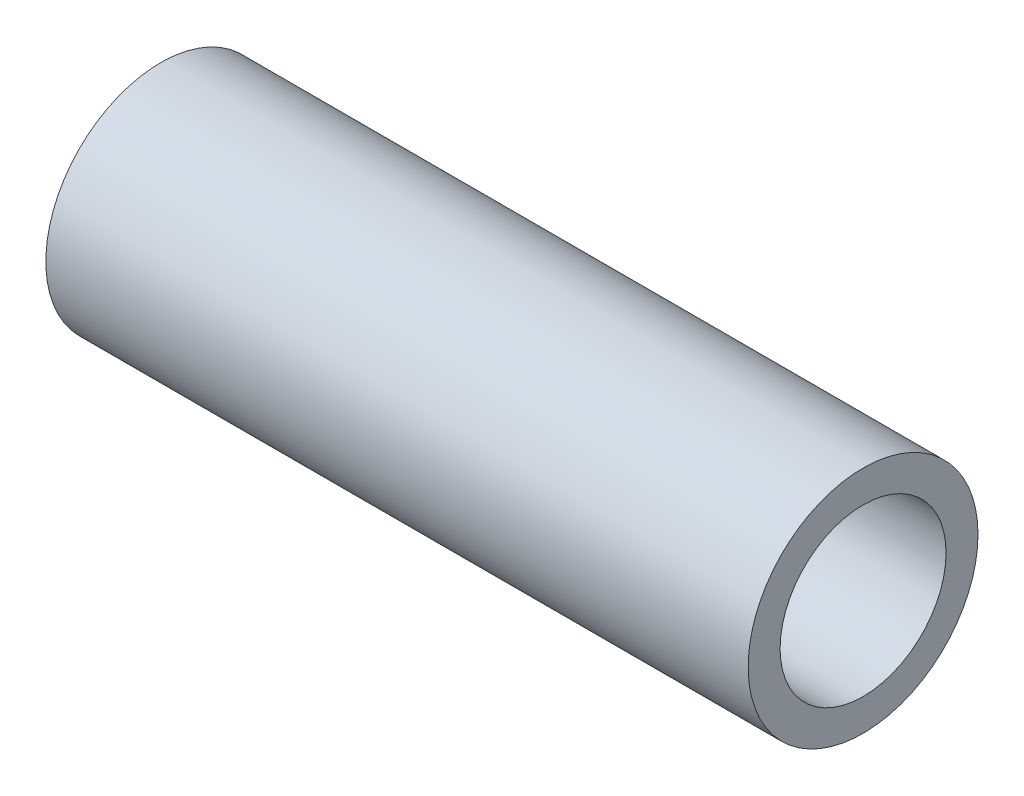
SolidWorks part; units mm, degrees
ref_plane "Front Plane" through (0, 0, 0) normal (0, 0, 1) x (1, 0, 0)
ref_plane "Top Plane" through (0, 0, 0) normal (0, 1, 0) x (1, 0, 0)
ref_plane "Right Plane" through (0, 0, 0) normal (1, 0, 0) x (0, 0, -1)
sketch "Sketch1" plane through (0, 0, 0) normal (1, 0, 0) x (0, 0, -1)
  circle A0 centre (0, 0) radius 6.5
  circle A1 centre (0, 0) radius 9
  dimension "D1" = 18
  dimension "D2" = 13
extrude "Boss-Extrude1" add sketch "Sketch1" along normal mid plane 55
